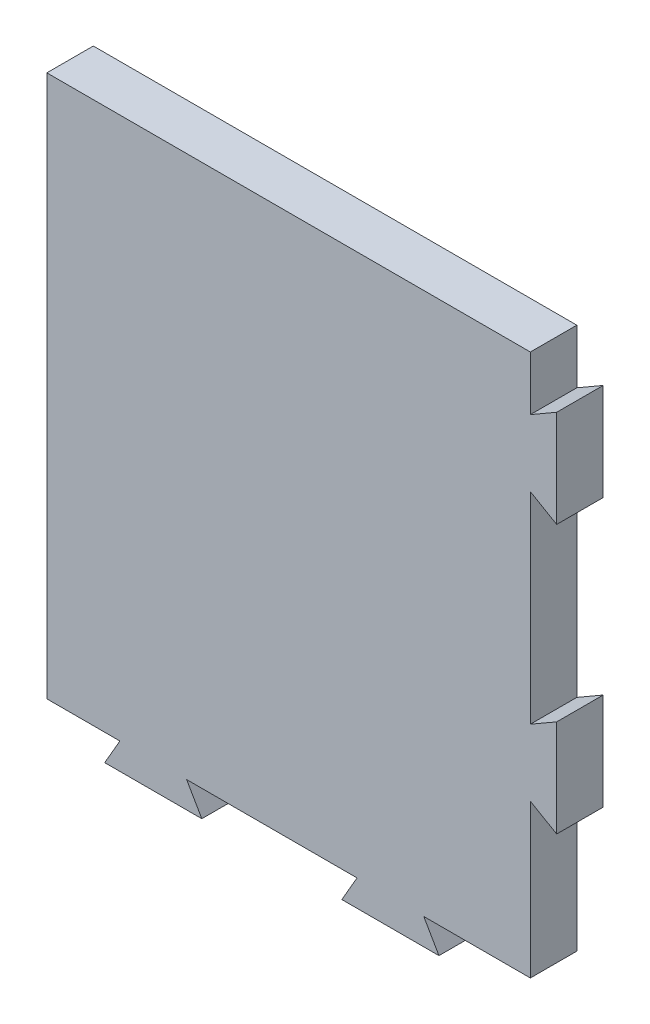
SolidWorks part; units mm, degrees
ref_plane "Alzado" through (0, 0, 0) normal (0, 0, 1) x (1, 0, 0)
ref_plane "Planta" through (0, 0, 0) normal (0, 1, 0) x (1, 0, 0)
ref_plane "Vista lateral" through (0, 0, 0) normal (1, 0, 0) x (0, 0, -1)
sketch "Croquis3" plane through (0, 0, 0) normal (0, 0, 1) x (1, 0, 0)
  line L0 (-13.8453, -15.5) -> (-15, -17.5) construction
  line L1 (13, -15.5) -> (-13, -15.5) construction
  line L2 (13, -15.5) -> (13, 15.5) construction
  line L3 (13, 15.5) -> (-13, 15.5) construction
  line L4 (-13, -15.5) -> (-13, 15.5) construction
  line L5 (13, -15.5) -> (-13, 15.5) construction
  line L6 (13, 15.5) -> (-13, -15.5) construction
  line L7 (-15, -17.5) -> (-7.6906, -17.5) construction
  line L8 (-7.6906, -17.5) -> (-8.8453, -15.5) construction
  line L9 (-8.8453, -15.5) -> (-13.8453, -15.5) construction
  line L10 (1.4641, -15.5) -> (0.3094, -17.5) construction
  line L11 (0.3094, -17.5) -> (7.6188, -17.5) construction
  line L12 (7.6188, -17.5) -> (6.4641, -15.5) construction
  line L13 (6.4641, -15.5) -> (1.4641, -15.5) construction
  line L14 (13, -5.9641) -> (15, -7.1188) construction
  line L15 (15, -7.1188) -> (15, 0.1906) construction
  line L16 (15, 0.1906) -> (13, -0.9641) construction
  line L17 (13, -0.9641) -> (13, -5.9641) construction
  line L18 (13, 16.3453) -> (15, 17.5) construction
  line L19 (15, 17.5) -> (15, 10.1906) construction
  line L20 (15, 10.1906) -> (13, 11.3453) construction
  line L21 (-13.5855, -15.65) -> (-14.4804, -17.2)
  line L22 (13, 11.3453) -> (13, 16.3453) construction
  line L23 (-14.4804, -17.2) -> (-8.2102, -17.2)
  line L24 (-15, -17.5) -> (15, -17.5) construction
  line L25 (-15, -17.5) -> (-15, 17.5) construction
  line L26 (-15, 17.5) -> (15, 17.5) construction
  line L27 (15, -17.5) -> (15, 17.5) construction
  line L28 (13, -15.5) -> (-18.2159, -15.5)
  line L29 (13, -15.5) -> (13, 19.5)
  line L30 (13, 19.5) -> (-18.2159, 19.5)
  line L31 (-18.2159, -15.5) -> (-18.2159, 19.5)
  line L32 (-8.2102, -17.2) -> (-9.1051, -15.65)
  line L33 (1.7239, -15.65) -> (0.829, -17.2)
  line L34 (0.829, -17.2) -> (7.0992, -17.2)
  line L35 (7.0992, -17.2) -> (6.2043, -15.65)
  line L36 (13.15, -5.7043) -> (14.7, -6.5992)
  line L37 (14.7, -6.5992) -> (14.7, -0.329)
  line L38 (14.7, -0.329) -> (13.15, -1.2239)
  line L39 (13.15, 16.0855) -> (14.7, 16.9804)
  line L40 (14.7, 16.9804) -> (14.7, 10.7102)
  line L41 (14.7, 10.7102) -> (13.15, 11.6051)
  line L42 (-13.5855, -15.65) -> (-13.4989, -15.5)
  line L43 (-9.1051, -15.65) -> (-9.1917, -15.5)
  line L44 (6.2043, -15.65) -> (6.1177, -15.5)
  line L45 (1.7239, -15.65) -> (1.8105, -15.5)
  line L46 (13.15, 11.6051) -> (13, 11.6917)
  line L47 (13.15, 16.0855) -> (13, 15.9989)
  line L48 (13.15, -5.7043) -> (13, -5.6177)
  line L49 (13.15, -1.2239) -> (13, -1.3105)
  point P0 (0, 0)
  dimension "D1" = 2
  dimension "D2" = 2
  dimension "D3" = 2
  dimension "D4" = 120
  dimension "D5" = 120
  dimension "D6" = 120
  dimension "D7" = 120
  dimension "D8" = 120
  dimension "D9" = 120
  dimension "D10" = 35
  dimension "D11" = 30
  dimension "D12" = 5
  dimension "D13" = 120
  dimension "D14" = 120
  dimension "D15" = 5
  dimension "D16" = 5
  dimension "D17" = 5
  dimension "D18" = 10
  dimension "D19" = 8
  dimension "D20" = 2
  dimension "D21" = 31.2159
  dimension "D24" = 35
  dimension "D22" = 0.3
  dimension "D23" = 0.3
extrude "Saliente-Extruir3" add sketch "Croquis3" along normal mid plane 3 contours L31 L28 L29 L30 | L32 L43 L28 L42 L21 L23 | L45 L33 L34 L35 L44 L28 | L39 L47 L29 L46 L41 L40 | L38 L49 L29 L48 L36 L37
